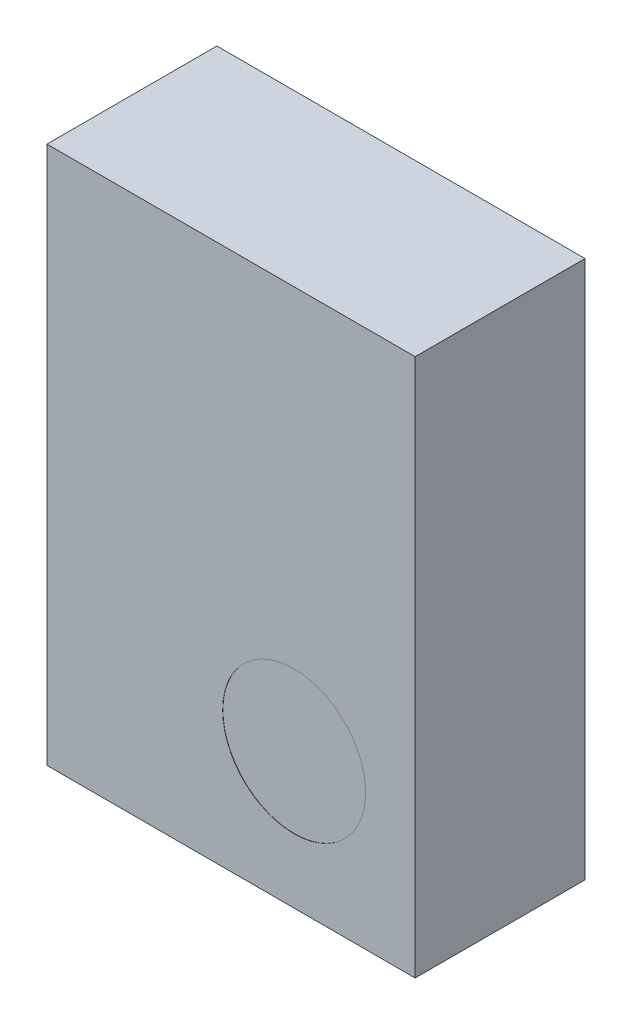
SolidWorks part; units mm, degrees
ref_plane "Front Plane" through (0, 0, 0) normal (0, 0, 1) x (1, 0, 0)
ref_plane "Top Plane" through (0, 0, 0) normal (0, 1, 0) x (1, 0, 0)
ref_plane "Right Plane" through (0, 0, 0) normal (1, 0, 0) x (0, 0, -1)
sketch "Sketch1" plane through (0, 0, 0) normal (0, 1, 0) x (1, 0, 0)
  line L1 (-20.6375, -9.525) -> (20.6375, -9.525)
  line L2 (-20.6375, -9.525) -> (-20.6375, 9.525)
  line L3 (-20.6375, 9.525) -> (20.6375, 9.525)
  line L4 (20.6375, -9.525) -> (20.6375, 9.525)
  line L5 (-20.6375, -9.525) -> (20.6375, 9.525) construction
  line L6 (-20.6375, 9.525) -> (20.6375, -9.525) construction
  point P0 (0, 0)
  dimension "D1" = 41.275
  dimension "D2" = 19.05
extrude "Boss-Extrude1" add sketch "Sketch1" along normal blind 60.325
sketch "Sketch2" plane through (0, 0, 9.525) normal (0, 0, 1) x (1, 0, 0)
  circle A0 centre (7.0735, 15.227) radius 8.0125
extrude "Cut-Extrude1" cut sketch "Sketch2" against normal blind 0.0254
